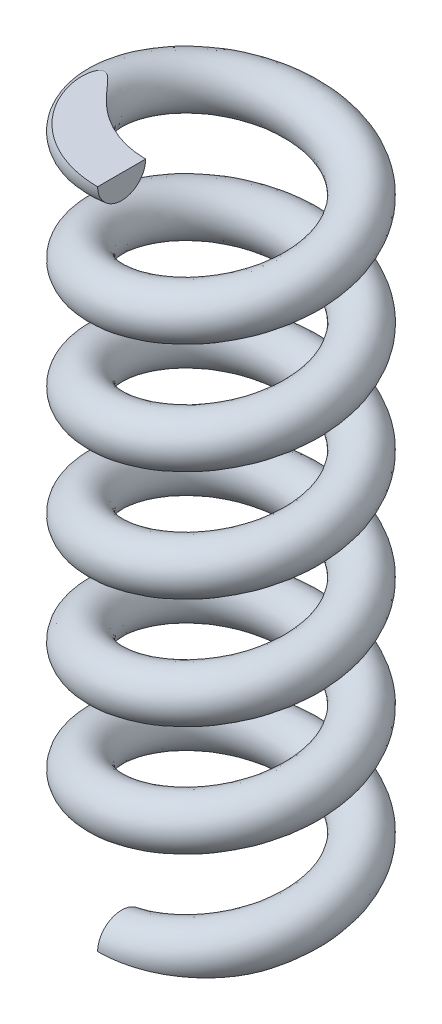
SolidWorks part; units mm, degrees
ref_plane "Front Plane" through (0, 0, 0) normal (0, 0, 1) x (1, 0, 0)
ref_plane "Top Plane" through (0, 0, 0) normal (0, 1, 0) x (1, 0, 0)
ref_plane "Right Plane" through (0, 0, 0) normal (1, 0, 0) x (0, 0, -1)
sketch "Sketch12" plane through (0, 0, 0) normal (0, 1, 0) x (1, 0, 0)
  circle A0 centre (0, 0) radius 15
  dimension "D1" = 30
curve "Helix/Spiral5" pitch 16.6667 height 100 turns 6
sketch "Sketch13" plane through (0, 0, 0) normal (1, 0, 0) x (0, 0, -1)
  circle A0 centre (-15, -100) radius 3.625
  spline S0 degree 3 poles (-15, 0) (-15, -0.3219) (-14.3227, -0.9717) (-11.4093, -1.9415) (-6.9844, -2.9127) (-1.6343, -3.8835) (3.9323, -4.8544) (8.9779, -5.8252) (12.8343, -6.7961) (14.9904, -7.767) (15.1606, -8.7379) (13.3225, -9.7087) (9.7194, -10.6796) (4.8288, -11.6505) (-0.7015, -12.6214) (-6.1389, -13.5922) (-10.7631, -14.5631) (-13.9614, -15.534) (-15.3101, -16.5049) (-14.6307, -17.4757) (-12.0131, -18.4466) (-7.804, -19.4175) (-2.5611, -20.3883) (3.0211, -21.3592) (8.2031, -22.3301) (12.2983, -23.301) (14.7644, -24.2718) (15.2745, -25.2427) (13.7611, -26.2136) (10.4248, -27.1845) (5.7074, -28.1553) (0.2339, -29.1262) (-5.2705, -30.0971) (-10.0768, -31.068) (-13.5481, -32.0388) (-15.2246, -33.0097) (-14.8843, -33.9806) (-12.5721, -34.9515) (-8.5945, -35.9223) (-3.4783, -36.8932) (2.0987, -37.8641) (7.3977, -38.835) (11.7166, -39.8058) (14.4834, -40.7767) (15.3315, -41.7476) (14.1486, -42.7184) (11.0913, -43.6893) (6.5647, -44.6602) (1.1685, -45.6311) (-4.3826, -46.6019) (-9.353, -47.5728) (-13.0845, -48.5437) (-15.0825, -49.5146) (-15.0825, -50.4854) (-13.0845, -51.4563) (-9.353, -52.4272) (-4.3826, -53.3981) (1.1685, -54.3689) (6.5647, -55.3398) (11.0913, -56.3107) (14.1486, -57.2816) (15.3315, -58.2524) (14.4834, -59.2233) (11.7166, -60.1942) (7.3977, -61.165) (2.0987, -62.1359) (-3.4783, -63.1068) (-8.5945, -64.0777) (-12.5721, -65.0485) (-14.8843, -66.0194) (-15.2246, -66.9903) (-13.5481, -67.9612) (-10.0768, -68.932) (-5.2705, -69.9029) (0.2339, -70.8738) (5.7074, -71.8447) (10.4248, -72.8155) (13.7611, -73.7864) (15.2745, -74.7573) (14.7644, -75.7282) (12.2983, -76.699) (8.2031, -77.6699) (3.0211, -78.6408) (-2.5611, -79.6117) (-7.804, -80.5825) (-12.0131, -81.5534) (-14.6307, -82.5243) (-15.3101, -83.4951) (-13.9614, -84.466) (-10.7631, -85.4369) (-6.1389, -86.4078) (-0.7015, -87.3786) (4.8288, -88.3495) (9.7194, -89.3204) (13.3225, -90.2913) (15.1606, -91.2621) (14.9904, -92.233) (12.8343, -93.2039) (8.9779, -94.1748) (3.9323, -95.1456) (-1.6343, -96.1165) (-6.9844, -97.0873) (-11.4093, -98.0585) (-14.3227, -99.0283) (-15, -99.6781) (-15, -100) knots 0 0 0 0 0.009709 0.019417 0.029126 0.038835 0.048544 0.058252 0.067961 0.07767 0.087379 0.097087 0.106796 0.116505 0.126214 0.135922 0.145631 0.15534 0.165049 0.174757 0.184466 0.194175 0.203883 0.213592 0.223301 0.23301 0.242718 0.252427 0.262136 0.271845 0.281553 0.291262 0.300971 0.31068 0.320388 0.330097 0.339806 0.349515 0.359223 0.368932 0.378641 0.38835 0.398058 0.407767 0.417476 0.427184 0.436893 0.446602 0.456311 0.466019 0.475728 0.485437 0.495146 0.504854 0.514563 0.524272 0.533981 0.543689 0.553398 0.563107 0.572816 0.582524 0.592233 0.601942 0.61165 0.621359 0.631068 0.640777 0.650485 0.660194 0.669903 0.679612 0.68932 0.699029 0.708738 0.718447 0.728155 0.737864 0.747573 0.757282 0.76699 0.776699 0.786408 0.796117 0.805825 0.815534 0.825243 0.834951 0.84466 0.854369 0.864078 0.873786 0.883495 0.893204 0.902913 0.912621 0.92233 0.932039 0.941748 0.951456 0.961165 0.970874 0.980583 0.990291 1 1 1 1 construction
  dimension "D1" = 7.25
sweep "Sweep1" add profiles "Sketch13" path "Helix/Spiral5"
sketch "Sketch14" plane through (0, 0, 0) normal (0, 1, 0) x (1, 0, 0)
  circle A0 centre (0, 0) radius 20
  dimension "D1" = 40
extrude "Cut-Extrude1" cut sketch "Sketch14" along normal blind 10 contours A0
sketch "Sketch15" plane through (0, 0, 0) normal (0, 0, 1) x (1, 0, 0)
  line L0 (-12.7993, -50.1281) -> (13.9939, -50.1281) construction
ref_plane "Plane1" through (0, -100, 0) normal (0, 1, 0) x (1, 0, 0)
sketch "Sketch16" plane through (0, -100, 0) normal (0, 1, 0) x (1, 0, 0)
  circle A0 centre (0, 0) radius 20
  dimension "D1" = 40
extrude "Cut-Extrude2" cut sketch "Sketch16" against normal blind 10
sketch "Sketch17" plane through (0, 0, 0) normal (0, 0, 1) x (1, 0, 0)
  line L0 (0, 0) -> (0, -100) construction
  line L1 (20.8036, -100) -> (-20.8036, -100) construction
  spline S0 degree 3 poles (0, 0) (-1.8202, -0.3219) (-5.4941, -0.9717) (-10.2508, -1.9415) (-13.6565, -2.9127) (-15.2513, -3.8835) (-14.8261, -4.8544) (-12.4367, -5.8252) (-8.3998, -6.7961) (-3.2501, -7.767) (2.3302, -8.7379) (7.6017, -9.7087) (11.8662, -10.6796) (14.5588, -11.6505) (15.3226, -12.6214) (14.0566, -13.5922) (10.9285, -14.5631) (6.3526, -15.534) (0.9351, -16.5049) (-4.6062, -17.4757) (-9.5374, -18.4466) (-13.205, -19.4175) (-15.1233, -20.3883) (-15.0382, -21.3592) (-12.9609, -22.3301) (-9.1666, -23.301) (-4.1579, -24.2718) (1.4016, -25.2427) (6.7754, -26.2136) (11.2516, -27.1845) (14.2373, -28.1553) (15.3369, -29.1262) (14.4047, -30.0971) (11.5643, -31.068) (7.1919, -32.0388) (1.8667, -33.0097) (-3.7057, -33.9806) (-8.7872, -34.9515) (-12.7047, -35.9223) (-14.9391, -36.8932) (-15.1944, -37.8641) (-13.4369, -38.835) (-9.8993, -39.8058) (-5.0503, -40.7767) (0.4678, -41.7476) (5.9238, -42.7184) (10.5951, -43.6893) (13.8629, -44.6602) (15.2941, -45.6311) (14.6992, -46.6019) (12.1571, -47.5728) (8.0045, -48.5437) (2.7914, -49.5146) (-2.7914, -50.4854) (-8.0045, -51.4563) (-12.1571, -52.4272) (-14.6992, -53.3981) (-15.2941, -54.3689) (-13.8629, -55.3398) (-10.5951, -56.3107) (-5.9238, -57.2816) (-0.4678, -58.2524) (5.0503, -59.2233) (9.8993, -60.1942) (13.4369, -61.165) (15.1944, -62.1359) (14.9391, -63.1068) (12.7047, -64.0777) (8.7872, -65.0485) (3.7057, -66.0194) (-1.8667, -66.9903) (-7.1919, -67.9612) (-11.5643, -68.932) (-14.4047, -69.9029) (-15.3369, -70.8738) (-14.2373, -71.8447) (-11.2516, -72.8155) (-6.7754, -73.7864) (-1.4016, -74.7573) (4.1579, -75.7282) (9.1666, -76.699) (12.9609, -77.6699) (15.0382, -78.6408) (15.1233, -79.6117) (13.205, -80.5825) (9.5374, -81.5534) (4.6062, -82.5243) (-0.9351, -83.4951) (-6.3526, -84.466) (-10.9285, -85.4369) (-14.0566, -86.4078) (-15.3226, -87.3786) (-14.5588, -88.3495) (-11.8662, -89.3204) (-7.6017, -90.2913) (-2.3302, -91.2621) (3.2501, -92.233) (8.3998, -93.2039) (12.4367, -94.1748) (14.8261, -95.1456) (15.2513, -96.1165) (13.6565, -97.0873) (10.2508, -98.0585) (5.4941, -99.0283) (1.8202, -99.6781) (0, -100) knots 0 0 0 0 0.009709 0.019417 0.029126 0.038835 0.048544 0.058252 0.067961 0.07767 0.087379 0.097087 0.106796 0.116505 0.126214 0.135922 0.145631 0.15534 0.165049 0.174757 0.184466 0.194175 0.203883 0.213592 0.223301 0.23301 0.242718 0.252427 0.262136 0.271845 0.281553 0.291262 0.300971 0.31068 0.320388 0.330097 0.339806 0.349515 0.359223 0.368932 0.378641 0.38835 0.398058 0.407767 0.417476 0.427184 0.436893 0.446602 0.456311 0.466019 0.475728 0.485437 0.495146 0.504854 0.514563 0.524272 0.533981 0.543689 0.553398 0.563107 0.572816 0.582524 0.592233 0.601942 0.61165 0.621359 0.631068 0.640777 0.650485 0.660194 0.669903 0.679612 0.68932 0.699029 0.708738 0.718447 0.728155 0.737864 0.747573 0.757282 0.76699 0.776699 0.786408 0.796117 0.805825 0.815534 0.825243 0.834951 0.84466 0.854369 0.864078 0.873786 0.883495 0.893204 0.902913 0.912621 0.92233 0.932039 0.941748 0.951456 0.961165 0.970874 0.980583 0.990291 1 1 1 1 construction
